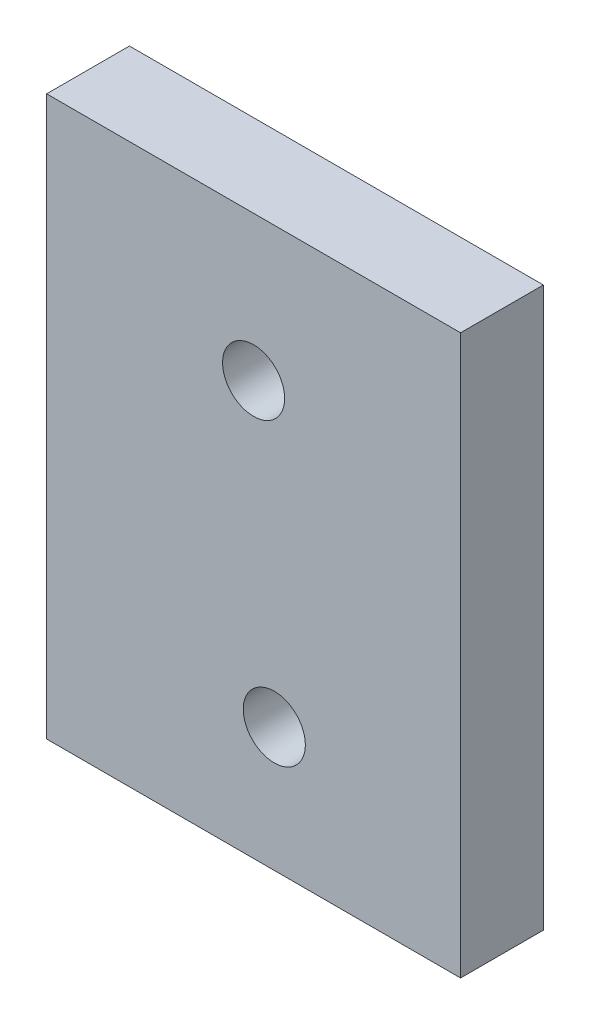
SolidWorks part; units mm, degrees
ref_plane "前视基准面" through (0, 0, 0) normal (0, 0, 1) x (1, 0, 0)
ref_plane "上视基准面" through (0, 0, 0) normal (0, 1, 0) x (1, 0, 0)
ref_plane "右视基准面" through (0, 0, 0) normal (1, 0, 0) x (0, 0, -1)
sketch "草图1" plane through (0, 0, 0) normal (0, 0, 1) x (1, 0, 0)
  line L0 (0, 13.5) -> (0, 6.5) construction
  line L1 (-10, -13.5) -> (10, -13.5)
  line L2 (-10, -13.5) -> (-10, 13.5)
  line L3 (-10, 13.5) -> (10, 13.5)
  line L4 (10, -13.5) -> (10, 13.5)
  line L5 (-10, -13.5) -> (10, 13.5) construction
  line L6 (-10, 13.5) -> (10, -13.5) construction
  circle A0 centre (1, -7.5) radius 1.5
  circle A1 centre (0, 6.5) radius 1.5
  point P0 (0, 0)
  dimension "D3" = 3
  dimension "D7" = 3
  dimension "D1" = 20
  dimension "D2" = 27
  dimension "D4" = 6
  dimension "D5" = 9
  dimension "D6" = 7
extrude "凸台-拉伸1" add sketch "草图1" along normal blind 4
